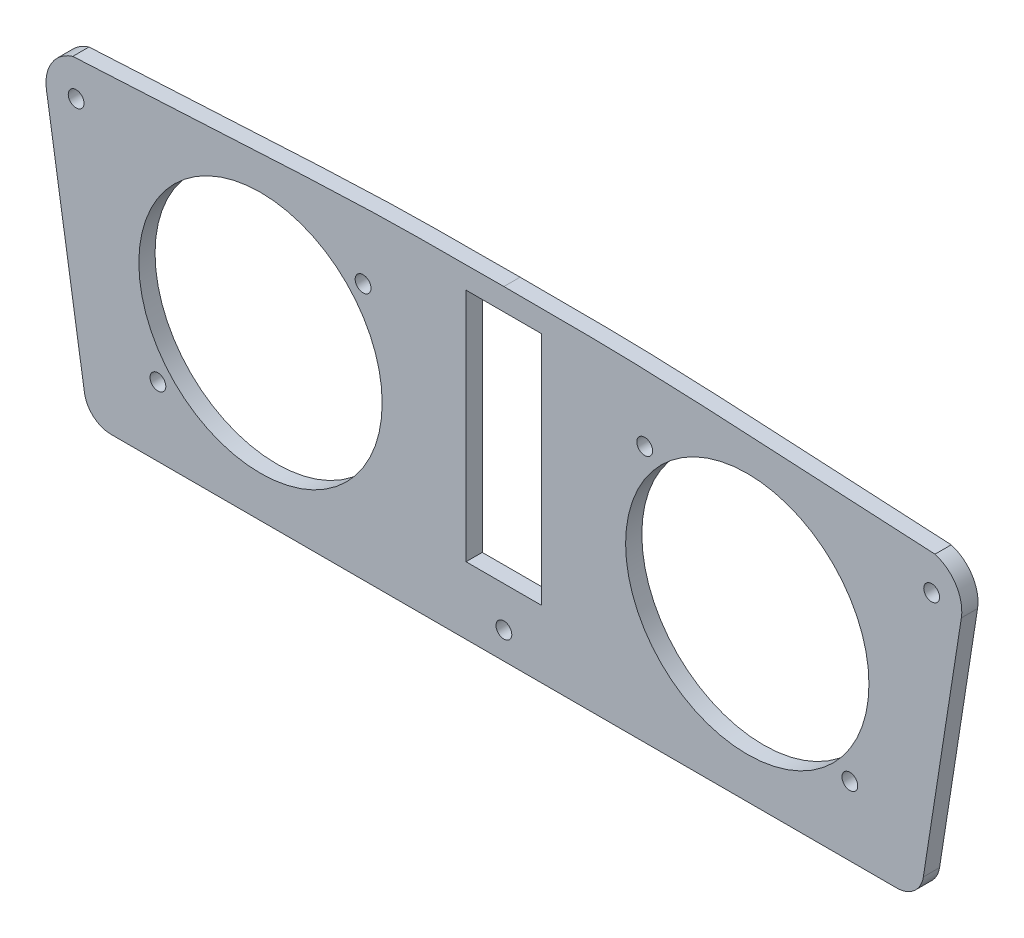
SolidWorks part; units mm, degrees
ref_plane "Alzado" through (0, 0, 0) normal (0, 0, 1) x (1, 0, 0)
ref_plane "Planta" through (0, 0, 0) normal (0, 1, 0) x (1, 0, 0)
ref_plane "Vista lateral" through (0, 0, 0) normal (1, 0, 0) x (0, 0, -1)
sketch "Croquis1" plane through (0, 0, 0) normal (0, 0, 1) x (1, 0, 0)
  line L0 (72.621, -42.7139) -> (-72.621, -42.7139)
  line L1 (79.7182, 14.2861) -> (-79.7182, 14.2861) construction
  line L2 (0, 14.2861) -> (0, 17.2861) construction
  line L3 (-77.7935, 17.2861) -> (77.7935, 17.2861) construction
  line L4 (0, -40.4126) -> (0, 34.1548) construction
  line L5 (-25, 41.2162) -> (-25, -46.3712) construction
  line L6 (-77.5611, -38.4855) -> (-84.5891, 6.5113)
  line L11 (25, 41.2162) -> (25, -46.3712) construction
  line L14 (77.5611, -38.4855) -> (84.5891, 6.5113)
  arc A0 (84.5891, 6.5113) -> (79.7182, 14.2861) centre (77.6729, 7.5915) ccw
  arc A1 (77.5611, -38.4855) -> (72.621, -42.7139) centre (72.621, -37.7139) cw
  arc A2 (-77.5611, -38.4855) -> (-72.621, -42.7139) centre (-72.621, -37.7139) ccw
  arc A3 (-84.5891, 6.5113) -> (-79.7182, 14.2861) centre (-77.6729, 7.5915) cw
  conic Q0 (79.7182, 14.2861) -> (0, 17.2861) control (25, 17.2861) rho 0.75
  conic Q1 (-79.7182, 14.2861) -> (0, 17.2861) control (-25, 17.2861) rho 0.75
  point P15 (-84.627, 12.5288)
  point P27 (0, -42.7139)
  point P28 (0, -42.7139)
  point P40 (0, 9.5288)
  point P61 (0, -42.7139)
  point P62 (84.627, 12.5288)
  dimension "D1" = 5
  dimension "D2" = 7
  dimension "D4" = 60
  dimension "D3" = 3
extrude "Saliente-Extruir3" add sketch "Croquis1" along normal blind 3 contours Q0 Q1 A3 L6 A2 L0 A1 L14 A0
sketch "Croquis10" plane through (0, 0, 0) normal (0, 0, -1) x (-1, 0, 0)
  line L0 (-79.1761, -2.225) -> (-70, 10.8116) construction
  line L1 (79.1761, -2.225) -> (70, 10.8116) construction
  line L2 (-20, 27.3642) -> (-20, -66.0706) construction
  line L3 (-89.1533, -2.1273) -> (92.9339, -3.91) construction
  line L4 (-70, 32.4884) -> (-70, -57.6963) construction
  line L5 (70, -55.635) -> (70, -62.635) construction
  line L6 (-80.637, 7.1286) -> (-73.609, -37.8682)
  line L7 (-72.621, -38.7139) -> (72.621, -38.7139)
  line L8 (73.609, -37.8682) -> (80.637, 7.1286)
  line L9 (-79.1761, -2.225) -> (-73.609, -37.8682) construction
  line L10 (-20, -38.7139) -> (-72.621, -38.7139) construction
  line L11 (73.609, -37.8682) -> (79.1761, -2.225) construction
  line L12 (0, -66.0706) -> (0, 45.5866) construction
  line L13 (20, 32.4884) -> (20, -73.2967) construction
  line L14 (10, 34.6369) -> (10, -62.635) construction
  line L15 (17, 23.9593) -> (17, 3.2579) construction
  line L16 (72.621, -38.7139) -> (20, -38.7139) construction
  line L17 (73.2713, -38.4736) -> (16.7387, 13.2106) construction
  line L18 (-73.2713, -38.4736) -> (-16.7387, 13.2106) construction
  line L19 (8.9875, 13.2106) -> (-8.9875, 13.2106)
  line L20 (-8.9875, 13.2106) -> (-8.9875, -12.6315)
  line L21 (-8.9875, -12.6315) -> (8.9875, -12.6315)
  line L22 (8.9875, 13.2106) -> (8.9875, -12.6315)
  line L23 (0, -42.7139) -> (0, -37.7139) construction
  line L24 (-72.621, -42.7139) -> (72.621, -42.7139) construction
  line L25 (0, -37.7139) -> (5.5196, -37.7139) construction
  line L26 (74.588, 4.2933) -> (83.6049, 11.3079) construction
  line L27 (-74.588, 4.2933) -> (-83.6049, 11.3079) construction
  circle A0 centre (45.005, -12.6315) radius 22.5
  circle A1 centre (45.005, -12.6315) radius 25.7 construction
  circle A2 centre (-45.005, -12.6315) radius 22.5
  arc A3 (84.5891, 6.5113) -> (79.7182, 14.2861) centre (77.6729, 7.5915) ccw construction
  arc A4 (-79.7182, 14.2861) -> (-84.5891, 6.5113) centre (-77.6729, 7.5915) ccw construction
  arc A8 (-78.9106, 10.3243) -> (-80.637, 7.1286) centre (-77.6729, 7.5915) ccw
  arc A9 (-73.609, -37.8682) -> (-72.621, -38.7139) centre (-72.621, -37.7139) ccw
  arc A10 (72.621, -38.7139) -> (73.609, -37.8682) centre (72.621, -37.7139) ccw
  arc A11 (80.637, 7.1286) -> (78.9106, 10.3243) centre (77.6729, 7.5915) ccw
  arc A13 (-73.609, -37.8682) -> (-72.621, -38.7139) centre (-72.621, -37.7139) ccw
  arc A14 (72.621, -38.7139) -> (73.609, -37.8682) centre (72.621, -37.7139) ccw construction
  spline S1 degree 2 poles (20, -38.7139) (0.4038, -11.4379) (17, 13.6086) knots 0 0 0 1 1 1 construction
  spline S2 degree 2 poles (-20, -38.7139) (-0.4038, -11.4379) (-17, 13.6086) knots 0 0 0 1 1 1 construction
  spline S4 degree 3 poles (2741.8019, 6043.6166) (1624.8077, -144.8373) (843.9136, -30.8574) (52.6222, 11.7513) (46.0499, 12.1034) (36.1891, 12.5892) (32.9019, 12.7438) (26.3256, 13.0031) (23.0364, 13.1028) (16.455, 13.2247) (13.1641, 13.2517) (-305.0431, 14.7382) (-620.6288, -91.7151) (-892.3164, 6878.2271) knots -29.599716 -29.599716 -29.599716 -29.599716 0.25 0.25 0.5 0.5 0.625 0.625 0.75 0.75 0.875 0.875 12.83635 12.83635 12.83635 12.83635 only from (78.9106, 10.3243) to (0, 13.2861)
  spline S5 degree 3 poles (468.6965, 896.6433) (312.9806, -13.5531) (151.4662, 14.0208) (-13.1641, 13.2517) (-16.455, 13.2247) (-23.0364, 13.1028) (-26.3256, 13.0031) (-32.9019, 12.7438) (-36.1891, 12.5892) (-46.0499, 12.1034) (-52.6222, 11.7513) (-374.041, -5.5562) (-688.2719, -34.056) (-1023.8404, 337.5944) knots -6.00309 -6.00309 -6.00309 -6.00309 0.125 0.125 0.25 0.25 0.375 0.375 0.5 0.5 0.75 0.75 12.726363 12.726363 12.726363 12.726363 only from (0, 13.2861) to (-78.9106, 10.3243)
  spline S6 degree 3 poles (70, 10.8116) (66.3982, 11.008) (62.7964, 11.2034) (52.6222, 11.7513) (46.0499, 12.1034) (36.1891, 12.5892) (32.9019, 12.7438) (26.3256, 13.0031) (23.0364, 13.1028) (18.7434, 13.1823) (17.741, 13.1977) (16.7387, 13.2106) knots 0.112988 0.112988 0.112988 0.112988 0.25 0.25 0.5 0.5 0.625 0.625 0.75 0.75 0.788074 0.788074 0.788074 0.788074 construction
  point P8 (-79.1761, -2.225)
  point P9 (-70, 10.8116)
  point P32 (20, 13.159)
  point P33 (20, -38.7139)
  point P38 (10, -3.098)
  point P51 (26.0372, 4.7096)
  point P52 (63.9727, -29.9726)
  point P53 (-26.0372, 4.7096)
  point P57 (-63.9727, -29.9726)
  point P63 (0, -12.6315)
  point P64 (0, 13.2106)
  point P74 (79.0965, 7.8006)
  point P75 (-74.588, 4.2933)
  point P81 (-79.0965, 7.8006)
  dimension "D9" = 45
  dimension "D10" = 51.4
  dimension "D2" = 70
  dimension "D3" = 70
  dimension "D6" = 20
  dimension "D7" = 10
  dimension "D11" = 5
  dimension "D1" = 4
sketch "Croquis12" plane through (0, 0, 3) normal (0, 0, 1) x (1, 0, 0)
  line L0 (8.9875, 13.2106) -> (-8.9875, 13.2106) construction
  line L1 (-8.9875, 13.2106) -> (-8.9875, -12.6315) construction
  line L2 (-8.9875, -12.6315) -> (8.9875, -12.6315) construction
  line L3 (8.9875, -12.6315) -> (8.9875, 13.2106) construction
  circle A0 centre (-45.005, -12.6315) radius 22.5
  circle A1 centre (45.005, -12.6315) radius 22.5
extrude "Cortar-Extruir1" cut sketch "Croquis12" against normal blind 3
hole_wizard "Taladro de margen para #32" positions "Croquis3D3" profile "Croquis13" hole size "#3" standard "Ansi Inch" end condition through all
sketch3d "Croquis3D3"
  point P0 (-26.0372, 4.7096, 0)
  point P3 (-63.9727, -29.9726, 0)
  point P6 (26.0372, 4.7096, 0)
  point P9 (63.9727, -29.9726, 0)
sketch "Croquis13" plane through (-26.0372, 4.7096, 0) normal (1, 0, 0) x (0, 1, 0)
  line L0 (0, 0) -> (0, 3)
  line L1 (0, 3) -> (1.4605, 3)
  line L2 (1.4605, 3) -> (1.4605, 0)
  line L5 (1.4605, 0) -> (0, 0)
  line L11 (0, -6.35) -> (0, 107.95) construction
  dimension "Diámetro de taladro hasta el siguiente" = 2.921
  dimension "Profundidad de taladro hasta el siguiente" = 3
hole_wizard "Taladro de margen para #33" positions "Croquis3D4" profile "Croquis14" hole size "#3" standard "Ansi Inch" end condition through all
sketch3d "Croquis3D4"
  point P0 (0, -37.7139, 0)
sketch "Croquis14" plane through (0, -37.7139, 0) normal (1, 0, 0) x (0, 1, 0)
  line L0 (0, 0) -> (0, 3)
  line L1 (0, 3) -> (1.4605, 3)
  line L2 (1.4605, 3) -> (1.4605, 0)
  line L5 (1.4605, 0) -> (0, 0)
  line L11 (0, -6.35) -> (0, 107.95) construction
  dimension "Diámetro de taladro hasta el siguiente" = 2.921
  dimension "Profundidad de taladro hasta el siguiente" = 3
hole_wizard "Taladro de margen para #34" positions "Croquis3D5" profile "Croquis15" hole size "#3" standard "Ansi Inch" end condition through all
sketch3d "Croquis3D5"
  point P0 (79.0965, 7.8006, 0)
  point P3 (-79.0965, 7.8006, 0)
sketch "Croquis15" plane through (79.0965, 7.8006, 0) normal (1, 0, 0) x (0, 1, 0)
  line L0 (0, 0) -> (0, 3)
  line L1 (0, 3) -> (1.4605, 3)
  line L2 (1.4605, 3) -> (1.4605, 0)
  line L5 (1.4605, 0) -> (0, 0)
  line L11 (0, -6.35) -> (0, 107.95) construction
  dimension "Diámetro de taladro hasta el siguiente" = 2.921
  dimension "Profundidad de taladro hasta el siguiente" = 3
sketch "Croquis16" plane through (0, 0, 3) normal (0, 0, 1) x (1, 0, 0)
  line L0 (0, 13.2106) -> (-7, 13.2106)
  line L2 (-8.9875, 13.2106) -> (8.9875, 13.2106) construction
  line L4 (-7, 13.2106) -> (-7, -30.2885)
  line L5 (-7, -30.2885) -> (7, -30.2885)
  line L6 (7, -30.2885) -> (7, 13.2106)
  line L7 (7, 13.2106) -> (0, 13.2106)
  dimension "D1" = 7
  dimension "D2" = 14
extrude "Cortar-Extruir2" cut sketch "Croquis16" against normal blind 10
